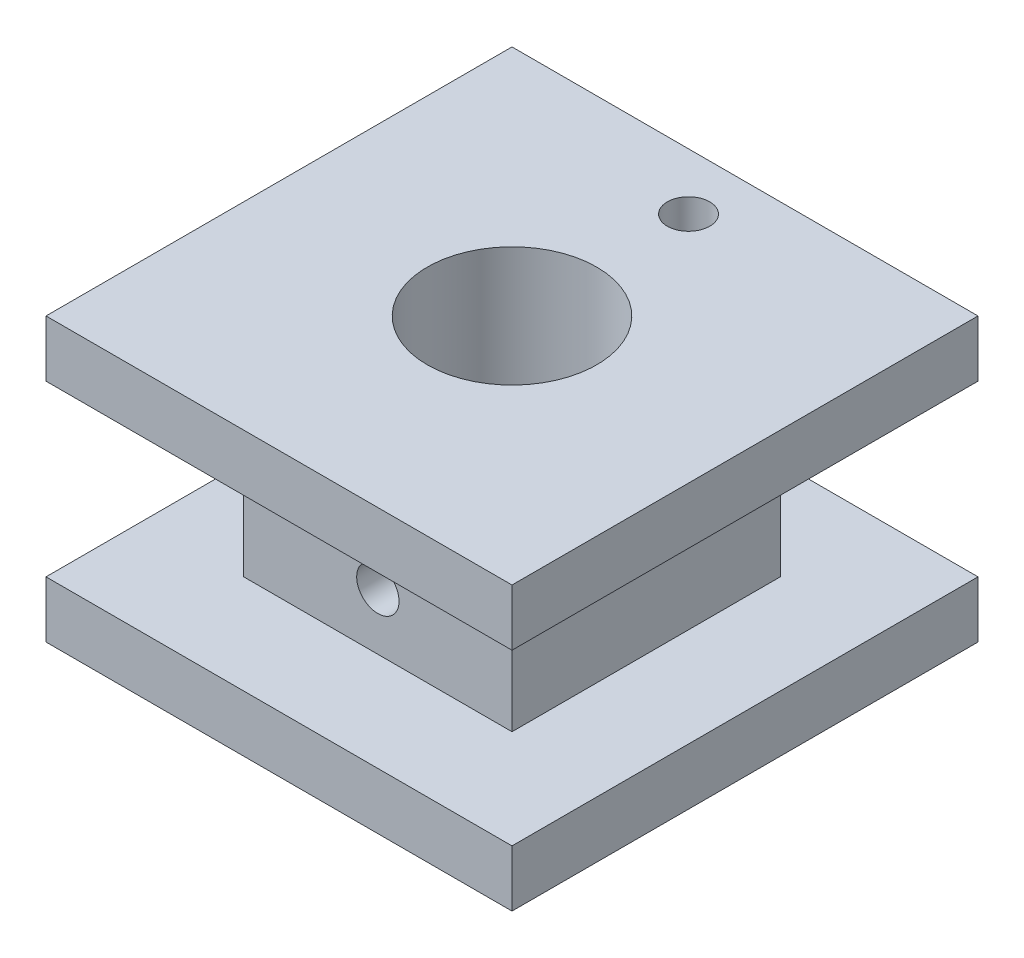
SolidWorks part; units mm, degrees
ref_plane "Front Plane" through (0, 0, 0) normal (0, 0, 1) x (1, 0, 0)
ref_plane "Top Plane" through (0, 0, 0) normal (0, 1, 0) x (1, 0, 0)
ref_plane "Right Plane" through (0, 0, 0) normal (1, 0, 0) x (0, 0, -1)
sketch "Sketch3" plane through (0, 0, 0) normal (0, 1, 0) x (1, 0, 0)
  line L1 (-16.5, -16.5) -> (16.5, -16.5)
  line L2 (-16.5, -16.5) -> (-16.5, 16.5)
  line L3 (-16.5, 16.5) -> (16.5, 16.5)
  line L4 (16.5, -16.5) -> (16.5, 16.5)
  line L5 (-16.5, -16.5) -> (16.5, 16.5) construction
  line L6 (-16.5, 16.5) -> (16.5, -16.5) construction
  point P0 (0, 0)
  dimension "D1" = 33
  dimension "D2" = 33
extrude "Boss-Extrude1" add sketch "Sketch3" along normal blind 20
sketch "Sketch4" plane through (0, 0, 16.5) normal (0, 0, 1) x (1, 0, 0)
  line L0 (-16.5, 20) -> (-16.5, 0) construction
  line L1 (-16.5, 10) -> (16.5, 10) construction
  line L2 (16.5, 20) -> (16.5, 0) construction
  line L3 (0, 0) -> (0, 20) construction
  line L4 (-16.5, 20) -> (16.5, 20) construction
  line L5 (0, 16) -> (0, 4) construction
  line L6 (-16.5, 4) -> (16.5, 4)
  line L7 (-16.5, 4) -> (-16.5, 16)
  line L8 (-16.5, 16) -> (16.5, 16)
  line L9 (16.5, 4) -> (16.5, 16)
  line L10 (-16.5, 4) -> (16.5, 16) construction
  line L11 (-16.5, 16) -> (16.5, 4) construction
  line L12 (-12.5, 16) -> (-12.5, 4) construction
  line L13 (6.5, 16) -> (6.5, 4) construction
  point P11 (0, 10)
  dimension "D1" = 12
  dimension "D2" = 19
  dimension "D3" = 4
  dimension "D4" = 10
extrude "Cut-Extrude1" cut sketch "Sketch4" against normal blind 7
mirror "Mirror7" about plane through (0, 0, 0) normal (1, 0, 0) of "Cut-Extrude1" second plane through (0, 0, 0) second plane normal (0, 0, 1)
sketch "Sketch6" plane through (16.5, 0, 0) normal (1, 0, 0) x (0, 0, -1)
  line L0 (0, 20) -> (0, 0) construction
  line L1 (-16.5, 20) -> (16.5, 20) construction
  line L2 (0, 0) -> (-9.5, 10) construction
  line L3 (-9.5, 4) -> (-9.5, 16) construction
  line L4 (-9.5, 10) -> (9.5, 10) construction
  line L5 (9.5, 4) -> (9.5, 16) construction
  line L7 (-9.5, 4) -> (9.5, 4)
  line L8 (-9.5, 4) -> (-9.5, 16)
  line L9 (-9.5, 16) -> (9.5, 16)
  line L10 (9.5, 4) -> (9.5, 16)
  line L11 (-9.5, 4) -> (9.5, 16) construction
  line L12 (-9.5, 16) -> (9.5, 4) construction
  point P5 (0, 10)
extrude "Cut-Extrude2" cut sketch "Sketch6" against normal blind 7
mirror "Mirror8" about plane through (0, 0, 0) normal (0, 0, 1) of "Cut-Extrude2" second plane through (0, 0, 0) second plane normal (1, 0, 0)
sketch "Sketch7" plane through (0, 20, 0) normal (0, 1, 0) x (1, 0, 0)
  line L0 (0, 16.5) -> (0, -16.5) construction
  line L1 (16.5, 16.5) -> (-16.5, 16.5) construction
  line L2 (-16.5, -16.5) -> (16.5, -16.5) construction
  line L3 (0, -16.5) -> (-16.5, 0) construction
  line L4 (-16.5, 16.5) -> (-16.5, -16.5) construction
  line L5 (-16.5, 0) -> (16.5, 0) construction
  line L6 (16.5, -16.5) -> (16.5, 16.5) construction
  circle A0 centre (0, 0) radius 6
  dimension "D1" = 12
extrude "Cut-Extrude3" cut sketch "Sketch7" against normal through all
sketch "Sketch9" plane through (0, 20, 0) normal (0, 1, 0) x (1, 0, 0)
  line L0 (0, 16.5) -> (0, -16.5) construction
  line L1 (16.5, 16.5) -> (-16.5, 16.5) construction
  line L2 (-16.5, -16.5) -> (16.5, -16.5) construction
  line L3 (0, -16.5) -> (-16.5, 0) construction
  line L4 (-16.5, 16.5) -> (-16.5, -16.5) construction
  line L5 (-16.5, 0) -> (16.5, 0) construction
  line L6 (16.5, -16.5) -> (16.5, 16.5) construction
  line L7 (-16.5, 12.5) -> (16.5, 12.5) construction
  circle A0 centre (0, 12.5) radius 1.5
  dimension "D1" = 4
extrude "Cut-Extrude5" cut sketch "Sketch9" against normal mid plane 15
sketch "Sketch10" plane through (0, 0, 9.5) normal (0, 0, 1) x (1, 0, 0)
  line L0 (0, 16) -> (0, 4) construction
  line L1 (16.5, 16) -> (-16.5, 16) construction
  line L2 (-9.5, 4) -> (9.5, 4) construction
  line L3 (0, 4) -> (-9.5, 10) construction
  line L4 (-9.5, 16) -> (-9.5, 4) construction
  line L5 (-9.5, 10) -> (9.5, 10) construction
  line L6 (9.5, 16) -> (9.5, 4) construction
  line L7 (-16.5, 4) -> (16.5, 4) construction
  circle A0 centre (0, 8) radius 1.5
  dimension "D1" = 4
extrude "Cut-Extrude9" cut sketch "Sketch10" against normal mid plane 8
